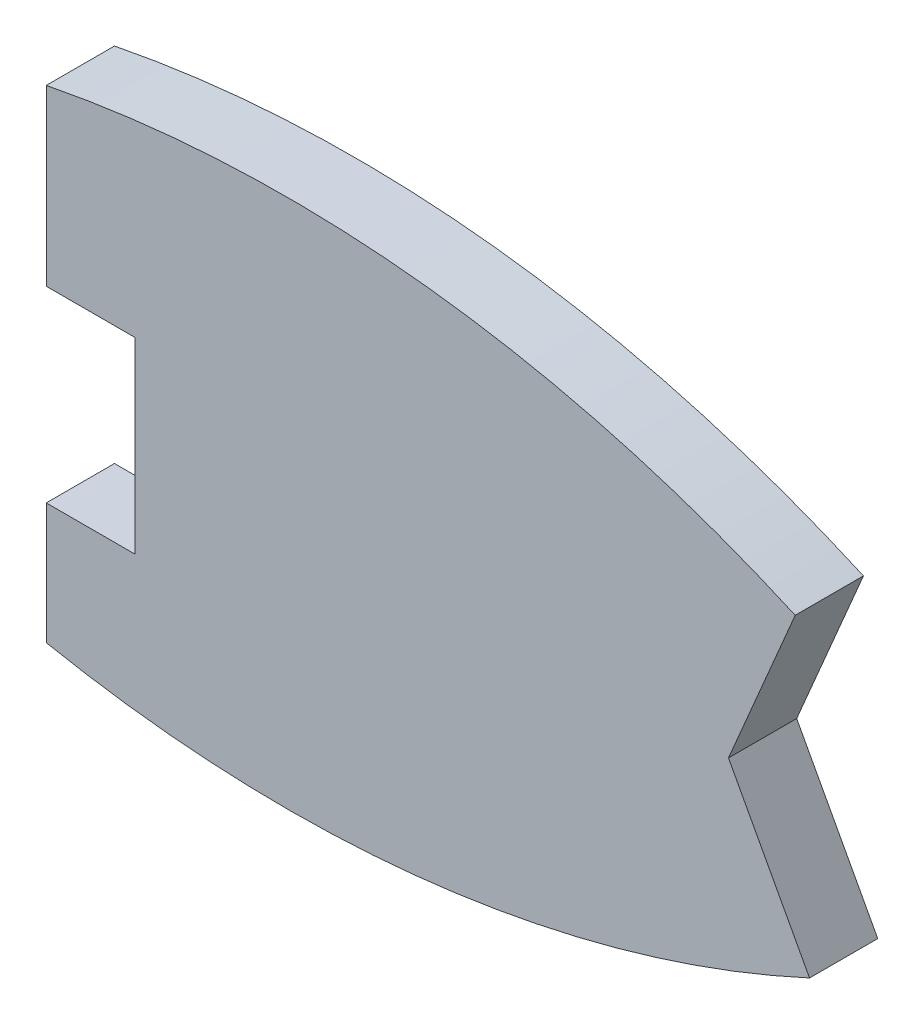
SolidWorks part; units mm, degrees
ref_plane "Ebene vorne" through (0, 0, 0) normal (0, 0, 1) x (1, 0, 0)
ref_plane "Ebene oben" through (0, 0, 0) normal (0, 1, 0) x (1, 0, 0)
ref_plane "Ebene rechts" through (0, 0, 0) normal (1, 0, 0) x (0, 0, -1)
sketch "Sketch1" plane through (0, 0, 0) normal (0, 0, 1) x (1, 0, 0)
  line L0 (0, 5.5) -> (-5.2, 5.5)
  line L1 (-5.2, 5.5) -> (-5.2, 15.7)
  line L2 (-5.2, 15.7) -> (-5.2, -12.6) construction
  line L3 (38.7148, 10.7519) -> (34.8, 1.55)
  line L4 (34.8, 1.55) -> (39.5532, -7.2481)
  line L5 (-5.2, 1.55) -> (49.8046, 1.55) construction
  line L6 (-5.2, -12.6) -> (-5.2, -5.5)
  line L7 (-5.2, -5.5) -> (0, -5.5)
  line L8 (0, -5.5) -> (0, 5.5)
  arc A0 (-5.2, 15.7) -> (38.7148, 10.7519) centre (8.9672, -55.9121) cw
  arc A1 (-5.2, -12.6) -> (39.5532, -7.2481) centre (8.9319, 59.019) ccw
  point P16 (0, 0)
  dimension "D7" = 73
  dimension "D1" = 11
  dimension "D2" = 10.2
  dimension "D3" = 7.1
  dimension "D4" = 18
  dimension "D5" = 10
  dimension "D6" = 40
  dimension "D8" = 5.2
  dimension "D9" = 43.9148
extrude "Boss-Extrude1" add sketch "Sketch1" along normal blind 4 contours A1 L4 L3 A0 L1 L0 L8 L7 L6
